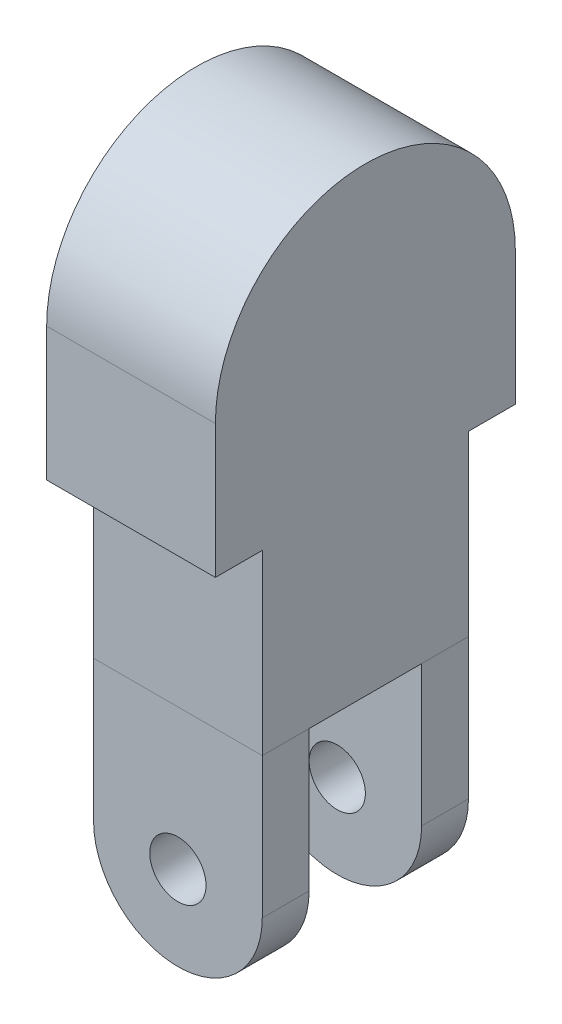
SolidWorks part; units mm, degrees
ref_plane "Front Plane" through (0, 0, 0) normal (0, 0, 1) x (1, 0, 0)
ref_plane "Top Plane" through (0, 0, 0) normal (0, 1, 0) x (1, 0, 0)
ref_plane "Right Plane" through (0, 0, 0) normal (1, 0, 0) x (0, 0, -1)
sketch "Sketch1" plane through (0, 0, 0) normal (0, 0, 1) x (1, 0, 0)
  line L0 (-4.5, 0) -> (-4.5, 7.5)
  line L5 (4.5, 0) -> (4.5, 7.5)
  line L6 (-4.5, 7.5) -> (4.5, 7.5)
  circle A0 centre (0, 0) radius 1.5
  circle A1 centre (0, 0) radius 4.5
  point P0 (0, 0)
  dimension "D3" = 3
  dimension "D4" = 9
  dimension "D1" = 7.5
  dimension "D2" = 7.5
extrude "Boss-Extrude1" add sketch "Sketch1" against normal blind 2.5 contours A1 A0 | A1 L5 L6 L0
sketch3d "3DSketch1"
  line L0 (0, 0, 0) -> (0, 0, -11)
  line L1 (0, 0, -11) -> (4.5, 0, -11)
  line L3 (0, 0, -11) -> (-4.5, 0, -11)
  dimension "D1" = 11
ref_plane "Plane1" through (0, 0, -11) normal (0, 0, -1) x (-1, 0, 0)
sketch "Sketch4" plane through (0, 0, -11) normal (0, 0, -1) x (-1, 0, 0)
  line L0 (-4.5, 0) -> (-4.5, 7.5)
  line L1 (4.5, 0) -> (4.5, 7.5)
  line L2 (-4.5, 7.5) -> (4.5, 7.5)
  circle A0 centre (0, 0) radius 4.5
  circle A1 centre (0, 0) radius 1.5
  dimension "D1" = 9
  dimension "D4" = 3
  dimension "D2" = 7.5
  dimension "D3" = 7.5
extrude "Boss-Extrude2" add sketch "Sketch4" against normal blind 2.5 separate body contours A0 A1 | A0 L1 L2 L0
sketch "Sketch5" plane through (0, 7.5, 0) normal (0, 1, 0) x (1, 0, 0)
  line L1 (4.5, 11) -> (-4.5, 11)
  line L2 (4.5, 11) -> (4.5, 0)
  line L3 (4.5, 0) -> (-4.5, 0)
  line L8 (-4.5, 11) -> (-4.5, 0)
extrude "Boss-Extrude3" add sketch "Sketch5" along normal blind 9.48 separate body
sketch "Sketch6" plane through (0, 16.98, 0) normal (0, 1, 0) x (1, 0, 0)
  line L0 (-4.5, 11) -> (-4.5, 13.5)
  line L1 (4.5, 0) -> (4.5, -2.5)
  line L3 (-4.5, 13.5) -> (4.5, 13.5)
  line L4 (-4.5, 13.5) -> (-4.5, -2.5)
  line L5 (-4.5, -2.5) -> (4.5, -2.5)
  line L6 (4.5, 13.5) -> (4.5, -2.5)
  line M3 (4.5, 0) -> (4.5, 11)
  line M4 (4.5, 11) -> (-4.5, 11)
  line M5 (-4.5, 11) -> (-4.5, 0)
  line M6 (-4.5, 0) -> (4.5, 0)
  dimension "D1" = 2.5
  dimension "D2" = 2.5
extrude "Boss-Extrude4" add sketch "Sketch6" along normal blind 7.11 separate body contours L6 L3 L0 M4 | M6 M3 M4 M5 | L4 L5 L1 M6
sketch "Sketch9" plane through (4.5, 0, 0) normal (1, 0, 0) x (0, 0, -1)
  line L0 (13.5, 24.09) -> (-2.5, 24.09) construction
  circle A0 centre (5.5, 24.09) radius 8
extrude "Boss-Extrude5" add sketch "Sketch9" against normal blind 9
